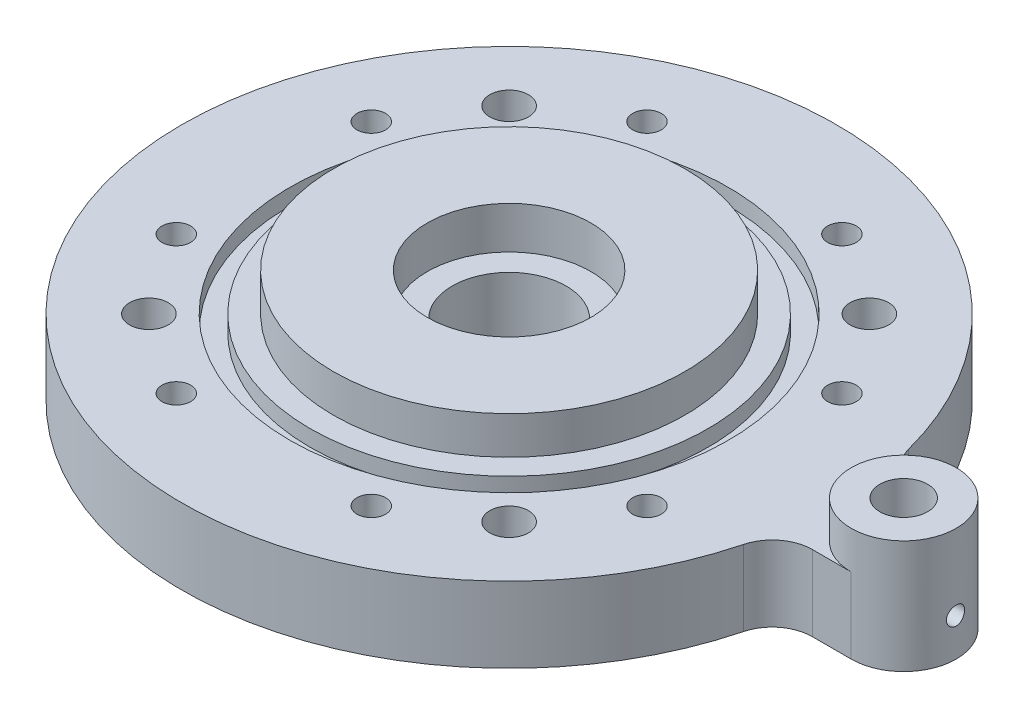
SolidWorks part; units mm, degrees
material "1060 Alloy"
ref_plane "Front" through (0, 0, 0) normal (0, 0, 1) x (1, 0, 0)
ref_plane "Top" through (0, 0, 0) normal (0, 1, 0) x (1, 0, 0)
ref_plane "Right" through (0, 0, 0) normal (1, 0, 0) x (0, 0, -1)
sketch "Sketch1" plane through (0, 0, 0) normal (0, 1, 0) x (1, 0, 0)
  line L0 (59.69, 0) -> (68.8572, 0) construction
  line L1 (62.0793, 9.1672) -> (68.8572, 9.1672)
  line L2 (62.0793, -9.1672) -> (68.8572, -9.1672)
  line L3 (59.69, 0) -> (78.0244, 0) construction
  line L4 (59.69, 0) -> (57.15, 0) construction
  arc A0 (55.3053, 14.403) -> (55.3053, -14.403) centre (0, 0) ccw
  circle A1 centre (0, 0) radius 57.15 construction
  arc A2 (68.8572, -9.1672) -> (68.8572, 9.1672) centre (68.8572, 0) ccw
  arc A3 (55.3053, 14.403) -> (62.0793, 9.1672) centre (62.0793, 16.1672) ccw
  arc A4 (62.0793, -9.1672) -> (55.3053, -14.403) centre (62.0793, -16.1672) ccw
  point P5 (34.5422, 0)
  point P10 (56.41, 9.1672)
  dimension "D1" = 114.3
  dimension "D4" = 7
  dimension "D2" = 18.3344
  dimension "D3" = 18.3344
  dimension "D5" = 2.54
extrude "base" add sketch "Sketch1" along normal blind 13.175
sketch "Sketch2" plane through (0, 13.175, 0) normal (0, 1, 0) x (1, 0, 0)
  line L0 (68.8572, 9.1672) -> (68.8572, -9.1672) construction
  circle A0 centre (0, 0) radius 30.6705
  arc A1 (68.8572, -9.1672) -> (68.8572, 9.1672) centre (68.8572, 0) ccw construction
  circle A2 centre (68.8572, 0) radius 9.1672
  circle A3 centre (68.8572, 0) radius 4.1672
  dimension "D1" = 61.341
  dimension "D2" = 8.3344
sketch "Sketch3" plane through (0, 0, 0) normal (0, -1, 0) x (1, 0, 0)
  line L0 (0, 0) -> (78.0244, 0) construction
  line L1 (0, 0) -> (40.4112, -40.4112) construction
  circle A0 centre (0, 0) radius 44.45 construction
  circle A1 centre (-31.4309, -31.4309) radius 3.3734
  circle A2 centre (-31.4309, 31.4309) radius 3.3734
  circle A3 centre (31.4309, 31.4309) radius 3.3734
  circle A4 centre (31.4309, -31.4309) radius 3.3734
  arc A5 (68.8572, -9.1672) -> (68.8572, 9.1672) centre (68.8572, 0) ccw construction
  arc A6 (55.3053, 14.403) -> (55.3053, -14.403) centre (0, 0) ccw construction
  point P14 (0, 0)
  dimension "D1" = 88.9
  dimension "D2" = 6.7469
  dimension "D4" = 45
  dimension "D3" = 4
extrude "square bolt holes" cut sketch "Sketch3" against normal through all
sketch "Sketch4" plane through (0, 13.175, 0) normal (0, 1, 0) x (1, 0, 0)
  line L0 (0, 0) -> (0, 44.45) construction
  line L1 (0, 44.45) -> (0, 0) construction
  line L2 (0, 0) -> (17.0103, 41.0664) construction
  circle A0 centre (0, 0) radius 44.45 construction
  circle A1 centre (17.0103, 41.0664) radius 2.5
  dimension "D1" = 88.9
  dimension "D3" = 5
  dimension "D2" = 22.5
extrude "housing bolts" cut sketch "Sketch4" against normal blind 44.33
pattern_circular "CirPattern1" count 8 over 360 about axis through (0, 0, 0) along (0, 1, 0) of "housing bolts"
extrude "impeller cavity riser" add sketch "Sketch2" along normal blind 6.59
sketch "Sketch5" plane through (0, 19.765, 0) normal (0, 1, 0) x (1, 0, 0)
  circle A0 centre (0, 0) radius 14.2875
  dimension "D1" = 28.575
extrude "seal bore" cut sketch "Sketch5" against normal blind 7.35
sketch "Sketch6" plane through (0, 12.415, 0) normal (0, 1, 0) x (1, 0, 0)
  circle A0 centre (0, 0) radius 9.9375
  dimension "D1" = 19.875
extrude "bore" cut sketch "Sketch6" against normal blind 39.3
sketch "pressure tap plane alignment" plane through (0, 0, 0) normal (0, -1, 0) x (1, 0, 0)
  line L1 (0, 0) -> (57.15, 0) construction
  line L2 (57.15, 0) -> (57.15, 57.15) construction
  line L3 (57.15, 57.15) -> (0, 57.15) construction
  circle A0 centre (0, 0) radius 57.15 construction
  circle A1 centre (0, 0) radius 57.15 construction
ref_plane "pressure tap plane" through (57.15, 0, 0) normal (1, 0, 0) x (0, 0, -1)
sketch "Sketch9" plane through (57.15, 0, 0) normal (1, 0, 0) x (0, 0, -1)
  line L0 (0, 0) -> (0, 13.175) construction
  line L1 (57.15, 13.175) -> (-57.15, 13.175) construction
  circle A0 centre (0, 6.5875) radius 1.5875
  dimension "D1" = 3.175
extrude "pressure tap" cut sketch "Sketch9" against normal blind 57.15 and the other way through all
sketch "Sketch10" plane through (0, 13.175, 0) normal (0, 1, 0) x (1, 0, 0)
  circle A0 centre (68.8572, 0) radius 1.5875
  dimension "D1" = 3.175
extrude "pressure tap vertical hole" cut sketch "Sketch10" against normal blind 8.175
sketch "Sketch12" plane through (0, 13.175, 0) normal (0, 1, 0) x (1, 0, 0)
  circle A0 centre (0, 0) radius 34.7218
  circle A1 centre (0, 0) radius 38.2524
  dimension "D1" = 76.5048
  dimension "D2" = 69.4436
extrude "o ring feature" cut sketch "Sketch12" against normal blind 2.8245
equation "\"de\"= 0.43in\t\t\t'entrance eye diameter"
equation "\"d2\"= 2.1in \t\t\t'outer diameter of the impeller"
equation "\"d_exit\"= 0.18in \t\t'throat aka d1"
equation "\"theta\"= 12\t\t\t'angle of blades from inner to outer "
equation "\"impeller upper clearance\"= .5mm"
equation "\"impeller horizontal clearance\"= (\"d2\"*1.15 - \"d2\")/2 \t\t'clearance based on D2-D3 ratio for circular volute, ranges 1.15 to 1.2"
equation "\"impeller bottom clearance\"= .5mm"
equation "\"impeller base thickness\"= 2mm"
equation "\"impeller dowel diameter\"= 2mm"
equation "\"impeller bolt head diameter\"= \"m4 head bore diameter\""
equation "\"impeller bolt head depth\"= 4mm"
equation "\"impeller bolt stop depth\"= 3mm"
equation "\"impeller bolt bore\"= \"m4 clearance\""
equation "\"impeller shaft bore depth\"= 12mm"
equation "\"impeller shaft bore\"= 8mm"
equation "\"impeller boss depth\"= \"impeller shaft bore depth\"+\"impeller bolt stop depth\"+\"impeller bolt head depth\"-\"impeller base thickness\""
equation "\"impeller boss diameter\"= \"upper seal ID\""
equation "\"impeller dowel length\"= 2mm*2 + \"impeller shaft bore\""
equation "\"coupler motor shaft hole ID\"= 8mm"
equation "\"coupler OD\"= 17mm"
equation "\"coupler length\"= 25mm"
equation "\"motor OD\"= 64mm"
equation "\"motor shaft diameter\"= 8mm"
equation "\"motor shaft pride\"= 32mm"
equation "\"motor to bearing plate distance\"= \"motor shaft pride\" + 2mm +\"coupler length\"/2"
equation "\"square plate bolt bore\"= \"m8 clearance\""
equation "\"square plate bolt head diameter\"= 13.5mm"
equation "\"square plate bolt pattern diameter\"= 3.5in"
equation "\"motor mount center bore\"= \"coupler OD\"+ 4mm"
equation "\"motor mount post radius\"= ( 3 * \"square plate bolt bore\" ) / 2"
equation "\"motor mount m4 screw hole diameter\"= 4mm"
equation "\"motor mount m4 head diameter\"= 7.25mm"
equation "\"motor mount m4 head depth\"= 4mm"
equation "\"motor mount m4 pattern diamater\"= 30mm"
equation "\"motor mount plate thickness\"= 8mm + \"motor mount m4 head depth\""
equation "\"shaft coupler section diameter\"= 8mm"
equation "\"shaft coupler section length\"= \"motor to bearing plate distance\" - \"motor shaft pride\" - 2mm"
equation "\"shaft bearing section diameter\"= \"bearing ID\""
equation "\"shaft bearing section length\"= \"bearing plate stop depth\" + \"bearing depth\""
equation "\"shaft bearing stop diameter\"= \"bearing ID\" + 4mm"
equation "\"shaft bearing stop length\"= 3mm"
equation "\"impeller cavity center height\"= \"impeller bottom clearance\" + \"impeller upper clearance\" + \"impeller center height\""
equation "\"impeller cavity diameter\"= 2 * \"impeller horizontal clearance\" + \"d2\" \t\t\t\t\t\t\t\t\t'called D3 analytically"
equation "\"impeller cavity outer height\"= \"impeller bottom clearance\" + \"impeller upper clearance\" + \"impeller base thickness\" + \"b2\" \t\t'this is height at impeller diameter d2, not at d3"
equation "\"impeller housing thickness\"= \"impeller housing exit threaded diameter\" + 2*\"impeller housing outlet grip\""
equation "\"impeller housing diameter\"= 4.5in"
equation "\"impeller housing bolt count\"= 8"
equation "\"impeller housing bolt diameter\"= \"m6 clearance\""
equation "\"impeller housing bolt pattern diameter\"= 3.5in"
equation "\"impeller housing threaded inlet diameter\"= 0.71875in \t'this is the 23/32 drill size for 1/2 NPT fitting https://www.mcmaster.com/#50715k269/=176pljy"
equation "\"impeller housing threaded inlet depth\"= .6in"
equation "\"impeller housing exit threaded diameter\"= 0.515625in \t\t'this is the 33/64 drill size for 9/16-18 fitting, expecting swagelok SS-8FK0-1-6STH fitting"
equation "\"impeller housing exit threaded depth\"= 10mm"
equation "\"impeller housing diffuser conical angle\"=10"
equation "\"impeller housing diffuser tangent angle\"=5"
equation "\"impeller housing outlet grip\"= 5mm"
equation "\"D1@Sketch1\"=\"impeller housing diameter\""
equation "\"D1@base\" = \"upper seal plate thickness\""
equation "\"D1@Sketch2\"=\"impeller cavity diameter\""
equation "\"D1@Sketch3\"=\"square plate bolt pattern diameter\""
equation "\"D2@Sketch3\"=\"m8 tap\""
equation "\"D1\"= \"upper seal plate thickness\" - 2mm"
equation "\"D1@Sketch4\"=\"impeller housing bolt pattern diameter\""
equation "\"D2@Sketch4\"=360/\"impeller housing bolt count\"/2"
equation "\"D3@Sketch4\"=\"m6 tap\""
equation "\"D1@CirPattern1\"=\"impeller housing bolt count\""
equation "\"D1@impeller cavity riser\" = \"upper seal plate riser\""
equation "\"D1@Sketch5\" = \"upper seal OD\""
equation "\"D1@seal bore\" = \"upper seal bore\""
equation "\"D1@Sketch6\" = \"upper seal ID\" + 4mm"
equation "\"D1@Sketch9\" = \"upper seal plate pressure hole diameter\""
equation "\"D1@pressure tap\"=\"impeller housing diameter\"/2"
equation "\"de_length\"= 4mm\t\t'entrance eye consistent length"
equation "\"square plate bolt head depth\"= 8mm"
equation "\"shaft impeller section diameter\"= \"impeller shaft bore\""
equation "\"shaft impeller section length\"= \"upper seal plate thickness\" + \"upper seal plate riser\" + \"impeller bottom clearance\" + \"impeller base thickness\" - \"impeller bolt head depth\" - \"impeller bolt stop depth\""
equation "\"impeller housing diffuser final diameter\"= .38in\t\t'aka d2'"
equation "\"D2@Sketch1\" = \"upper seal plate pressure tap diameter\" + \"upper seal plate pressure tap grip\" * 2"
equation "\"D3@Sketch1\" = \"upper seal plate pressure tap diameter\" + \"upper seal plate pressure tap grip\" * 2"
equation "\"D2@pressure tap\"=\"big seal plate pressure tap diameter\"/2+\"big seal plate pressure tap grip\""
equation "\"D2@Sketch2\" = \"upper seal plate pressure tap diameter\""
equation "\"D1@Sketch10\" = \"upper seal plate pressure hole diameter\""
equation "\"D1@pressure tap vertical hole\"= \"upper seal plate thickness\" / 2 + \"upper seal plate pressure hole diameter\" / 2"
equation "\"end mill size\"= 0.375in\t'for 3/8 endmill"
equation "\"m6 clearance\"= 0.234375in\t'this is 15/64 bit = 5.95mm, could use 6mm bit, B bit for 6.04mm or 1/4 bit for 6.35mm"
equation "\"m6 tap\"= 5mm\t\t\t'5mm is appropriate, could use 13/64 or #5,6,7"
equation "\"m6 head bore diameter\"= 11mm\t\t"
equation "\"m6 head bore depth\"= 7mm\t'actual is 6mm"
equation "\"m8 clearance\"= 0.3125in\t'this is 5/16in for 7.93mm, could use 8mm, O,P, or 21/64"
equation "\"m8 tap\"= 0.265625in\t\t'this is 17/64 for 6.746875mm"
equation "\"m8 head bore diameter\"= 14mm"
equation "\"m8 head bore depth\"= 9mm\t'actual is 8mm"
equation "\"ce\"= 3.14*\"de\"\t\t'entrance eye circumference"
equation "\"s_open\"= \"av\"/\"b1\"\t\t'width of open area"
equation "\"impeller center height\"= \"impeller base thickness\" + \"b1\"\t'impeller height at de"
equation "\"impeller outer height\"= \"impeller base thickness\" + \"b2\"\t'impeller height at de"
equation "\"lower seal OD\"= .917in\t\t'this is https://www.mcmaster.com/#9281k121/=174001b"
equation "\"lower seal ID\"= .375in"
equation "\"lower seal depth\"= .625in + .218in"
equation "\"lower seal bore\"= \"lower seal depth\" + 1mm"
equation "\"upper seal OD\"= 1.125in\t'this is https://www.mcmaster.com/#5154t33/=173zuau, needs to be visually inspected before machining!"
equation "\"upper seal ID\"= 0.625in"
equation "\"upper seal depth\"= .25in\t'aka height; these values need to be confirmed by inspection!! We may want to compress the height."
equation "\"upper seal bore\"= \"upper seal depth\" + 1mm"
equation "\"lower seal plate lip depth\"= 2mm"
equation "\"lower seal plate lip ID\"= \"lower seal OD\" - 3mm"
equation "\"lower seal plate thickness\"= \"lower seal plate lip depth\" + \"lower seal bore\""
equation "\"shaft lower seal section diameter\"= \"lower seal ID\""
equation "\"shaft lower seal section length\"= \"lower seal plate thickness\" + 1mm"
equation "\"upper seal plate thickness\"= \"upper seal plate pressure hole diameter\"+10mm"
equation "\"upper seal plate lip ID\"= \"upper seal OD\" - 3mm"
equation "\"upper seal plate riser\"= 6.59mm \t\t'this number needs to be read from the housing file"
equation "\"upper seal plate pressure hole diameter\"= .125in\t'this is 1/8 drill "
equation "\"upper seal plate pressure tap diameter\"= .328125in \t'this is 21/64 drill for a 1/8 ANPT tap"
equation "\"upper seal plate pressure tap grip\"= 5mm\t\t'this is the area around the tap so it doesn't crack"
equation "\"upper seal plate pressure tap depth\"= 12mm"
equation "\"bearing OD\"= 30mm"
equation "\"bearing ID\"= 10mm"
equation "\"bearing depth\"= 9mm"
equation "\"bearing outer race thickness\"= 1mm"
equation "\"bearing inner race thickness\"= 1mm"
equation "\"bearing bore\"= \"bearing depth\" + 1mm"
equation "\"z\"= 8\t\t\t\t'number of blades"
equation "\"b2\"= .2in\t\t\t'tip height from disc surface at d2; slightly higher than d_exit"
equation "\"b1\"= \"b2\" + (\"d2\"/2 - \"de\"/2)*tan(\"theta\") \t\t\t'tip height from disc surface at inlet eye"
equation "\"ae\"= 3.14*(\"de\"^2)/4\t\t'entrance eye area'"
equation "\"av_ratio\"= .325\t\t'ratio of av/ae at N_s of 470, range is .275 to .375, .325 ideal. High ratio means bigger area means smaller blades"
equation "\"av\"= \"ae\"*\"av_ratio\"\t\t'area between just two blades"
equation "\"s\"=\"ce\" - \"z\"*\"s_open\""
equation "\"bearing plate stop ID\"= \"bearing OD\" - 4mm"
equation "\"bearing plate stop depth\"= 3mm"
equation "\"bearing plate thickness\"= \"bearing bore\" + \"bearing plate stop depth\" + \"shaft bearing stop length\""
equation "\"m4 clearance\"= 0.171875in \t'this is 11/64 bit for 4.36mm"
equation "\"m4 tap\"= 0.125in\t\t'this is 1/8 bit for 3.17mm"
equation "\"m4 head bore diameter\"= 7.5mm"
equation "\"m4 head bore depth\"= 5mm\t'actual is ~4mm"
equation "\"big o-ring thickness\"= .139in"
equation "\"big o-ring OD\"= 2.734in"
equation "\"big o-ring ID\"= 3.012in"
equation "\"big o-ring groove depth\"= \"big o-ring thickness\"*4/5"
equation "\"D1@Sketch12\"=\"big o-ring ID\""
equation "\"D2@Sketch12\"=\"big o-ring OD\""
equation "\"D1@o ring feature\" = \"big o-ring groove depth\""
equation "\"min blade thickness\"= .15in"
equation "\"diffuser cartridge OD\"=.75in"
equation "\"diffuser flange bolt pattern diameter\"= 1.4in"
